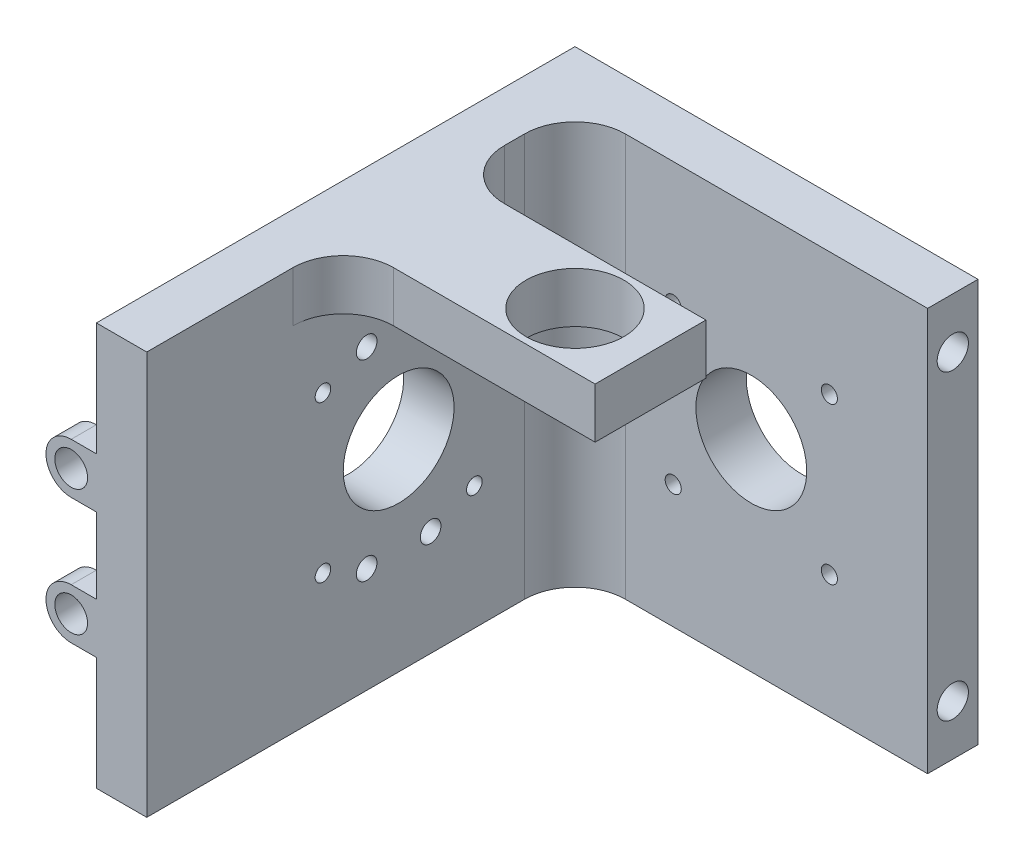
SolidWorks part; units mm, degrees
ref_plane "Front Plane" through (0, 0, 0) normal (0, 0, 1) x (1, 0, 0)
ref_plane "Top Plane" through (0, 0, 0) normal (0, 1, 0) x (1, 0, 0)
ref_plane "Right Plane" through (0, 0, 0) normal (1, 0, 0) x (0, 0, -1)
sketch "Sketch1" plane through (0, 0, 0) normal (0, 1, 0) x (1, 0, 0)
  line L0 (0, 45.5661) -> (0, -49.4339)
  line L1 (-10, 45.5661) -> (-10, -49.4339)
  line L2 (-10, 45.5661) -> (0, 45.5661)
  line L3 (-10, -49.4339) -> (0, -49.4339)
  dimension "D2" = 95
  dimension "D1" = 10
extrude "Boss-Extrude1" add sketch "Sketch1" along normal mid plane 80
sketch "Sketch2" plane through (-10, 0, 0) normal (-1, 0, 0) x (0, 0, 1)
  line L0 (49.4339, -40) -> (49.4339, 40) construction
  line L1 (-15.5912, 15.5) -> (-15.5912, -15.5) construction
  line L2 (-15.5912, -15.5) -> (14.4591, -15.5) construction
  line L3 (-45.5661, -40) -> (49.4339, -40) construction
  line L4 (14.4591, -15.5) -> (14.4591, 15.5) construction
  line L8 (14.4591, 15.5) -> (-15.5912, 15.5) construction
  line L9 (14.4591, 0) -> (-15.5912, 0) construction
  line L10 (5.7839, -19.05) -> (-6.9161, -19.05) construction
  line L11 (-0.5661, -15.5) -> (-0.5661, 15.5) construction
  line L12 (-6.9161, -19.05) -> (-6.9161, 19.05) construction
  line L15 (5.7839, -19.05) -> (5.7839, 19.05) construction
  line L16 (5.7839, -15.5) -> (5.7839, 15.5) construction
  line L17 (5.7839, 19.05) -> (-6.9161, 19.05) construction
  circle A0 centre (-0.5661, 0) radius 11
  circle A1 centre (-15.5912, -15.5) radius 1.55
  circle A2 centre (-6.9161, -19.05) radius 2.05
  circle A3 centre (-15.5912, 15.5) radius 1.55
  circle A4 centre (-6.9161, 19.05) radius 2.05
  circle A5 centre (5.7839, 19.05) radius 2.05
  circle A6 centre (14.4591, 15.5) radius 1.55
  circle A7 centre (14.4591, -15.5) radius 1.55
  circle A8 centre (5.7839, -19.05) radius 2.05
  point P2 (-16.0661, 0)
  point P3 (-16.0661, 50)
  point P8 (20.5839, 5.65)
  point P11 (-21.7161, 5.65)
  point P12 (20.5839, 44.35)
  point P13 (-21.7161, 44.35)
  point P14 (14.9339, 0)
  point P17 (14.9339, 50)
  point P26 (49.4339, 0)
  point P36 (49.4339, 19.1)
  point P37 (-15.5912, 19.1)
  dimension "D7" = 4.1
  dimension "D8" = 3.1
  dimension "D1" = 50
  dimension "D2" = 31
  dimension "D3" = 6.35
  dimension "D4" = 6.35
  dimension "D5" = 19.05
  dimension "D6" = 19.05
sketch "Sketch4" plane through (0, 0, 0) normal (1, 0, 0) x (0, 0, -1)
  line L0 (45.5661, 40) -> (45.5661, -40)
  line L1 (45.5661, -40) -> (35.5661, -40)
  line L3 (-49.4339, -40) -> (45.5661, -40) construction
  line L5 (35.5661, -40) -> (35.5661, 40)
  line L6 (-49.4339, 40) -> (45.5661, 40) construction
  line L7 (35.5661, 40) -> (45.5661, 40)
  dimension "D1" = 10
extrude "Boss-Extrude3" add sketch "Sketch4" along normal blind 70
sketch "Sketch10" plane through (0, 0, -45.5661) normal (0, 0, -1) x (-1, 0, 0)
  line L0 (-70, -40) -> (-70, 40) construction
  line L1 (-50.5, -40) -> (-50.5, 40) construction
  line L2 (-19.5, -40) -> (-19.5, 40) construction
  line L3 (-19.5, 40) -> (-50.5, 40) construction
  line L4 (-19.5, 15.5) -> (-50.5, 15.5) construction
  line L5 (-19.5, -15.5) -> (-50.5, -15.5) construction
  line L6 (-19.5, 0) -> (-50.5, 0) construction
  line L7 (-35, 15.5) -> (-35, -15.5) construction
  line L8 (10, 40) -> (10, -40) construction
  circle A0 centre (-35, 0) radius 11
  circle A1 centre (-19.5, 15.5) radius 1.6
  circle A2 centre (-50.5, 15.5) radius 1.6
  circle A3 centre (-19.5, -15.5) radius 1.6
  circle A4 centre (-50.5, -15.5) radius 1.6
  dimension "D5" = 3.2
  dimension "D3" = 24.5
  dimension "D1" = 45
  dimension "D2" = 31
  dimension "D4" = 31
extrude "Cut-Extrude1" cut sketch "Sketch10" against normal blind 10
extrude "Cut-Extrude2" cut sketch "Sketch2" against normal blind 10
sketch "Sketch14" plane through (0, 0, 49.4339) normal (0, 0, 1) x (1, 0, 0)
  line L0 (-10, -40) -> (-10, 40) construction
  line L1 (-10, 0) -> (-26.2162, 0) construction
  line L2 (-10, 12.5) -> (-26.2162, 12.5) construction
  line L3 (-10, -12.5) -> (-26.2162, -12.5) construction
  line L4 (-15, -12.5) -> (-15, 12.5) construction
  line L5 (-15, -17.5) -> (-10, -17.5)
  line L6 (-15, -40) -> (-15, 40) construction
  line L7 (-15, -7.5) -> (-10, -7.5)
  line L8 (-15, 7.5) -> (-10, 7.5)
  line L9 (-15, 17.5) -> (-10, 17.5)
  line L10 (-10, -17.5) -> (-10, -7.5)
  line L11 (-10, 7.5) -> (-10, 17.5)
  arc A0 (-15, -7.5) -> (-15, -17.5) centre (-15, -12.5) ccw
  arc A1 (-15, 17.5) -> (-15, 7.5) centre (-15, 12.5) ccw
  dimension "D4" = 5
  dimension "D1" = 12.5
  dimension "D2" = 12.5
  dimension "D3" = 5
extrude "Boss-Extrude4" add sketch "Sketch14" against normal blind 5
sketch "Sketch15" plane through (0, 0, 44.4339) normal (0, 0, -1) x (-1, 0, 0)
  line L0 (15, 12.5) -> (15, -12.5) construction
  line L1 (10, 7.5) -> (10, 17.5) construction
  circle A0 centre (15, -12.5) radius 3.25
  circle A1 centre (15, 12.5) radius 3.25
  dimension "D1" = 5
  dimension "D2" = 6.5
extrude "Cut-Extrude3" cut sketch "Sketch15" against normal blind 5
sketch "Croquis1" plane through (0, 40, 0) normal (0, 1, 0) x (1, 0, 0)
  line L0 (-10, -49.4339) -> (67.5667, -49.4339) construction
  line L1 (0, 0.5661) -> (50, 0.5661) construction
  line L2 (0, 11.5661) -> (0, -10.4339)
  line L3 (50, 11.5661) -> (50, -10.4339)
  line L4 (0, 11.5661) -> (50, 11.5661)
  line L5 (0, -10.4339) -> (50, -10.4339)
  line L6 (0, 35.5661) -> (0, -6.9339)
  line L7 (-10, 11.5661) -> (67.5667, 11.5661) construction
  line L8 (50, 39.5661) -> (50, -45.4339) construction
  line L9 (-10, 0.5661) -> (67.5667, 0.5661) construction
  line L10 (-10, -10.4339) -> (67.5667, -10.4339) construction
  line L11 (0, 39.5661) -> (0, -45.4339) construction
  line L12 (0, -49.4339) -> (0, 35.5661) construction
  line L13 (35, 11.5661) -> (35, -10.4339) construction
  line L15 (35, 35.5661) -> (35, -6.9339) construction
  circle A0 centre (35, 0.5661) radius 9.7234
  point P9 (0, -15)
  point P10 (70, -15)
  point P30 (35, 0.5661)
  dimension "D1" = 50
  dimension "D6" = 19.4469
  dimension "D2" = 50
  dimension "D3" = 11
  dimension "D4" = 11
  dimension "D5" = 35
extrude "Saliente-Extruir1" add sketch "Croquis1" against normal blind 10
sketch "Croquis2" plane through (70, 0, 0) normal (1, 0, 0) x (0, 0, -1)
  line L0 (45.5661, 40) -> (35.5661, 40) construction
  line L1 (45.5661, -40) -> (35.5661, -40) construction
  line L2 (35.5661, -40) -> (45.5661, -40) construction
  line L3 (35.5661, 40) -> (35.5661, -40) construction
  line L4 (45.5661, 30) -> (35.5661, 30) construction
  line L5 (45.5661, -30) -> (35.5661, -30) construction
  circle A0 centre (40.5661, 30) radius 3.1
  circle A1 centre (40.5661, -30) radius 3.1
  dimension "D3" = 6.2
  dimension "D1" = 10
  dimension "D2" = 10
extrude "Cortar-Extruir1" cut sketch "Croquis2" against normal blind 7
fillet "Redondeo1" radius 10 3 edges at (0, 35, -11.5661) (0, 35, 10.4339)
